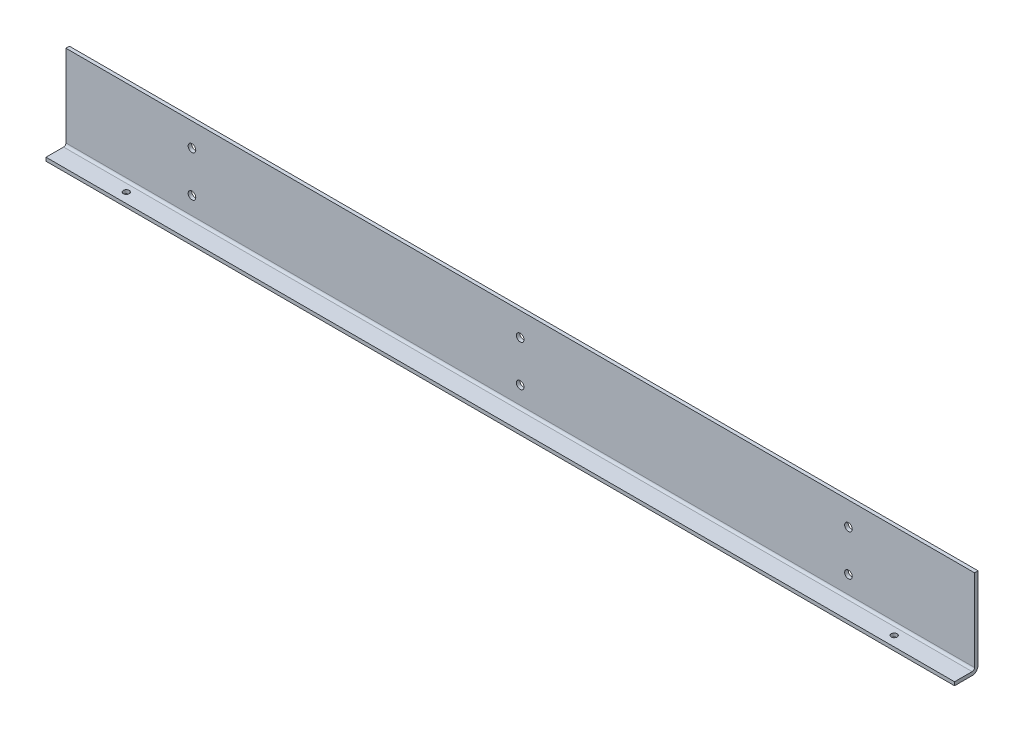
SolidWorks part; units mm, degrees
ref_plane "정면" through (0, 0, 0) normal (0, 0, 1) x (1, 0, 0)
ref_plane "윗면" through (0, 0, 0) normal (0, 1, 0) x (1, 0, 0)
ref_plane "우측면" through (0, 0, 0) normal (1, 0, 0) x (0, 0, -1)
sketch "스케치1" plane through (0, 0, 0) normal (0, 0, 1) x (1, 0, 0)
  line L1 (0, 0) -> (775, 0)
  line L2 (0, 0) -> (0, 75)
  line L3 (0, 75) -> (775, 75)
  line L4 (775, 0) -> (775, 75)
  dimension "D1" = 75
  dimension "D2" = 775
extrude "보스-돌출1" add sketch "스케치1" along normal blind 3
sketch "스케치2" plane through (0, 0, 3) normal (0, 0, 1) x (1, 0, 0)
  line L0 (775, 0) -> (775, 75) construction
  line L1 (0, 0) -> (775, 0)
  line L2 (0, 0) -> (0, 3)
  line L3 (0, 3) -> (775, 3)
  line L4 (775, 0) -> (775, 3)
  dimension "D1" = 3
extrude "보스-돌출2" add sketch "스케치2" along normal blind 20 from surface at -3 starting at face at (387.5, 37.5, 0)
sketch "스케치3" plane through (0, 0, 3) normal (0, 0, 1) x (1, 0, 0)
  line L0 (0, 75) -> (0, 3) construction
  line L1 (775, 0) -> (0, 0) construction
  circle A0 centre (107.5, 55) radius 3.25
  circle A1 centre (107.5, 20) radius 3.25
  circle A2 centre (387.5, 55) radius 3.25
  circle A3 centre (387.5, 20) radius 3.25
  circle A4 centre (667.5, 55) radius 3.25
  circle A5 centre (667.5, 20) radius 3.25
  point P14 (107.5, 46.8056)
  point P15 (471.6132, 15.4523)
  point P16 (471.6132, 46.8056)
  point P17 (0, 0)
  point P18 (0, 0)
  point P19 (0, 0)
  point P22 (0, 0)
  point P23 (0, 0)
  dimension "D6" = 6.5
  dimension "D1" = 107.5
  dimension "D2" = 280
  dimension "D3" = 280
  dimension "D4" = 20
  dimension "D5" = 55
  dimension "D7" = 387.5
extrude "컷-돌출1" cut sketch "스케치3" against normal through all
fillet "필렛1" radius 5 1 edges at (387.5, 0, 0)
sketch "스케치4" plane through (0, 3, 0) normal (0, 1, 0) x (1, 0, 0)
  line L0 (0, -20) -> (775, -20) construction
  line L1 (0, -20) -> (0, -3) construction
  circle A0 centre (60, -11.5) radius 2.5
  circle A1 centre (715, -11.5) radius 2.5
  point P6 (0, 0)
  point P7 (0, 0)
  point P12 (0, 0)
  dimension "D4" = 5
  dimension "D1" = 8.5
  dimension "D2" = 60
  dimension "D3" = 655
extrude "컷-돌출2" cut sketch "스케치4" against normal through all
fillet "필렛2" radius 2 1 edges at (387.5, 3, 3)
